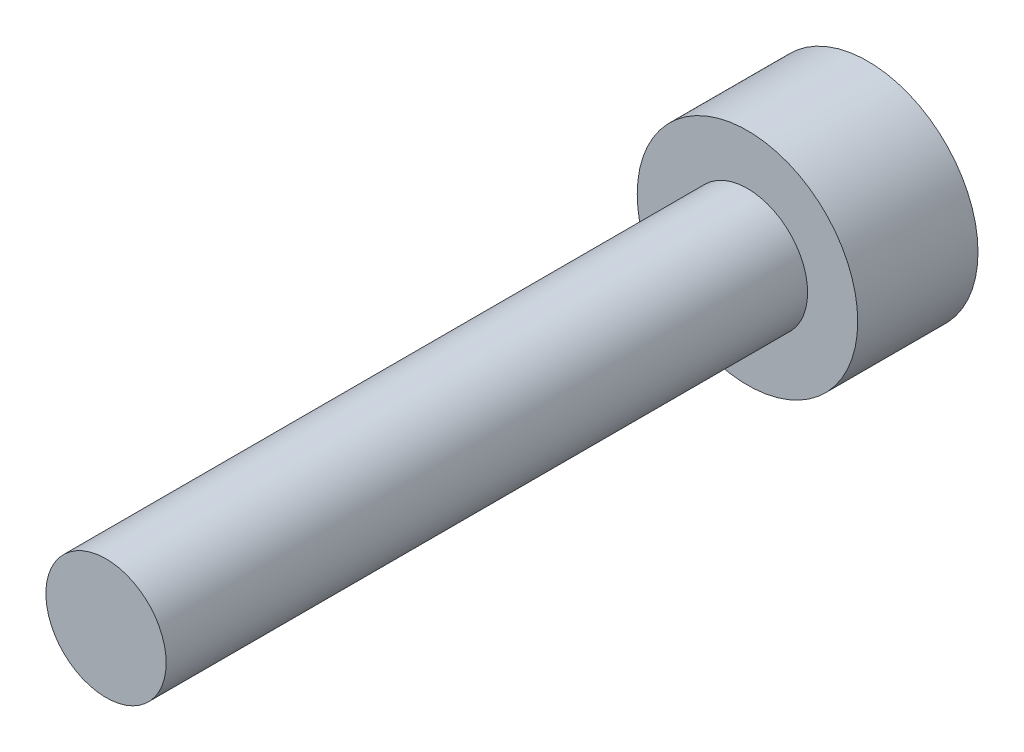
SolidWorks part; units mm, degrees
material "Acero aleado"
ref_plane "Alzado" through (0, 0, 0) normal (0, 0, 1) x (1, 0, 0)
ref_plane "Planta" through (0, 0, 0) normal (0, 1, 0) x (1, 0, 0)
ref_plane "Vista lateral" through (0, 0, 0) normal (1, 0, 0) x (0, 0, -1)
sketch "Croquis1" plane through (0, 0, 0) normal (0, 0, 1) x (1, 0, 0)
  circle A0 centre (0, 0) radius 2.75
  dimension "D1" = 5.5
extrude "Cabeza" add sketch "Croquis1" along normal blind 3 from offset 3
sketch "Croquis2" plane through (0, 0, 0) normal (0, 0, 1) x (1, 0, 0)
  circle A0 centre (0, 0) radius 1.5
  dimension "D1" = 3
extrude "Cuerpo" add sketch "Croquis2" along normal blind 16
sketch "Croquis3" plane through (0, 0, 0) normal (0, 0, 1) x (1, 0, 0)
  line L0 (1.4434, 0) -> (0.7217, 1.25)
  line L1 (0.7217, 1.25) -> (-0.7217, 1.25)
  line L2 (-0.7217, 1.25) -> (-1.4434, 0)
  line L3 (-1.4434, 0) -> (-0.7217, -1.25)
  line L4 (-0.7217, -1.25) -> (0.7217, -1.25)
  line L5 (0.7217, -1.25) -> (1.4434, 0)
  dimension "D1" = 1.4434
  dimension "D2" = 0.7217
  dimension "D3" = 1.25
  dimension "D4" = 0.7217
  dimension "D5" = 1.25
  dimension "D6" = 1.4434
  dimension "D7" = 0.7217
  dimension "D8" = 1.25
  dimension "D9" = 0.7217
  dimension "D10" = 1.25
extrude "Hexagono_interior" cut sketch "Croquis3" along normal blind 1.3 from offset 3
